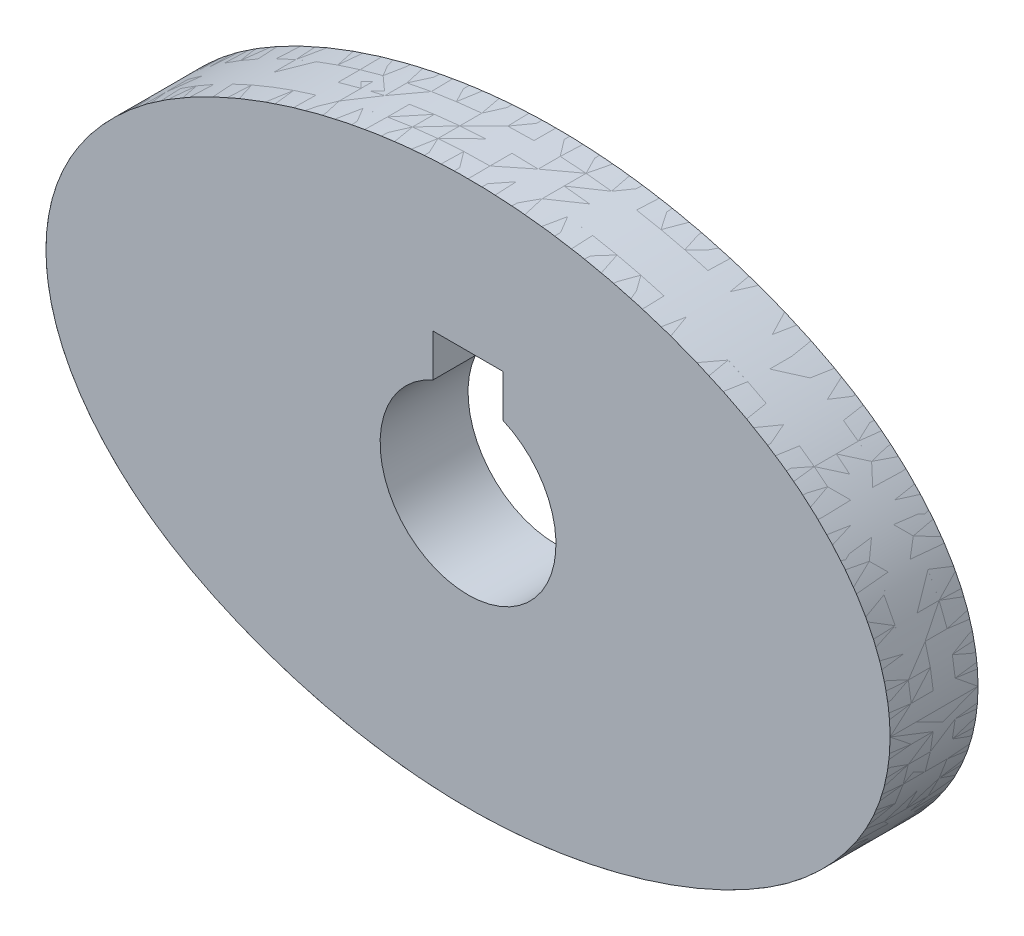
SolidWorks part; units mm, degrees
ref_plane "Alzado" through (0, 0, 0) normal (0, 0, 1) x (1, 0, 0)
ref_plane "Planta" through (0, 0, 0) normal (0, 1, 0) x (1, 0, 0)
ref_plane "Vista lateral" through (0, 0, 0) normal (1, 0, 0) x (0, 0, -1)
ref_plane "Plano1" through (0, 0, 0) normal (0, 0, -1) x (-1, 0, 0)
sketch "Croquis1" plane through (0, 0, 0) normal (0, 0, -1) x (-1, 0, 0)
  circle A0 centre (0, 0) radius 5
  spline S0 degree 3 poles (24, 0) (24, 2.5833) (23.04, 5.9933) (15.36, 12.6067) (8, 15.5) (-8, 15.5) (-15.36, 12.6067) (-23.04, 5.9933) (-24, 2.5833) (-24, 0) knots 0 0 0 0 0.25 0.25 0.5 0.5 0.75 0.75 1 1 1 1
  spline S1 degree 3 poles (-24, 0) (-24, -2.5833) (-23.04, -5.9933) (-15.36, -12.6067) (-8, -15.5) (8, -15.5) (15.36, -12.6067) (23.04, -5.9933) (24, -2.5833) (24, 0) knots 0 0 0 0 0.25 0.25 0.5 0.5 0.75 0.75 1 1 1 1
extrude "Saliente-Extruir1" add sketch "Croquis1" against normal blind 5
sketch "Croquis2" plane through (0, 0, 5) normal (0, 0, 1) x (1, 0, 0)
  spline S0 degree 3 poles (2536.1022, -1636.9675) (-332.2895, 89.1531) (67.0499, 31.904) (15.36, -12.6067) (8, -15.5) (-8, -15.5) (-15.36, -12.6067) (-67.0498, 31.904) (332.2883, 89.1529) (-2536.0896, -1636.9599) knots -2.865225 -2.865225 -2.865225 -2.865225 0.25 0.25 0.5 0.5 0.75 0.75 3.865221 3.865221 3.865221 3.865221 only from (24, 0) to (-24, 0) construction
  spline S1 degree 3 poles (-2536.1022, 1636.9675) (332.2895, -89.1531) (-67.0499, -31.904) (-15.36, 12.6067) (-8, 15.5) (8, 15.5) (15.36, 12.6067) (67.0498, -31.904) (-332.2883, -89.1529) (2536.0896, 1636.9599) knots -2.865225 -2.865225 -2.865225 -2.865225 0.25 0.25 0.5 0.5 0.75 0.75 3.865221 3.865221 3.865221 3.865221 only from (-24, 0) to (24, 0) construction
  spline S2 degree 3 poles (24, 0) (24, -2.5833) (23.04, -5.9933) (15.36, -12.6067) (8, -15.5) (-8, -15.5) (-15.36, -12.6067) (-23.04, -5.9933) (-24, -2.5833) (-24, 0) knots 0 0 0 0 0.25 0.25 0.5 0.5 0.75 0.75 1 1 1 1
  spline S3 degree 3 poles (-24, 0) (-24, 2.5833) (-23.04, 5.9933) (-15.36, 12.6067) (-8, 15.5) (8, 15.5) (15.36, 12.6067) (23.04, 5.9933) (24, 2.5833) (24, 0) knots 0 0 0 0 0.25 0.25 0.5 0.5 0.75 0.75 1 1 1 1
surface "Superficie-Extruir1" sketch "Croquis2" parameters "D1"=5
sketch "Croquis3" plane through (0, 0, 5) normal (0, 0, 1) x (1, 0, 0)
  line L1 (-2, 0) -> (2, 0)
  line L2 (-2, 0) -> (-2, 7)
  line L3 (-2, 7) -> (2, 7)
  line L4 (2, 0) -> (2, 7)
  circle A0 centre (0, 0) radius 5 construction
  circle A1 centre (0, 0) radius 5
  point P4 (0, 0)
  circle M4 centre (0, 0) radius 5
  dimension "D1" = 4
  dimension "D2" = 7
extrude "Cortar-Extruir1" cut sketch "Croquis3" against normal blind 10 contours L4 L3 L2 M4
